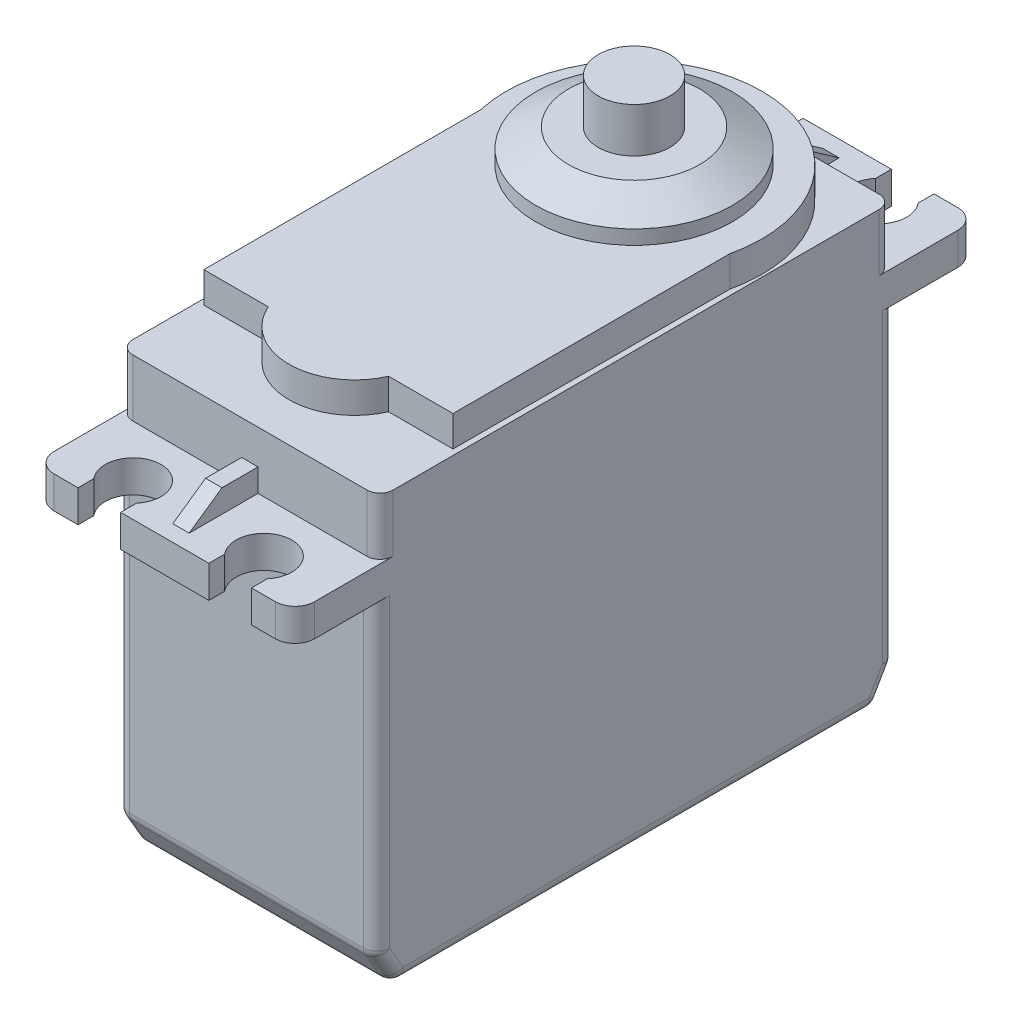
SolidWorks part; units mm, degrees
material "PA Type 6"
ref_plane "Front Plane" through (0, 0, 0) normal (0, 0, 1) x (1, 0, 0)
ref_plane "Top Plane" through (0, 0, 0) normal (0, 1, 0) x (1, 0, 0)
ref_plane "Right Plane" through (0, 0, 0) normal (1, 0, 0) x (0, 0, -1)
sketch "Sketch1" plane through (0, 0, 0) normal (0, 1, 0) x (1, 0, 0)
  line L1 (-10.0838, 10.1854) -> (10.0838, 10.1854)
  line L2 (-10.0838, 10.1854) -> (-10.0838, -30.0228)
  line L3 (-10.0838, -30.0228) -> (10.0838, -30.0228)
  line L4 (10.0838, 10.1854) -> (10.0838, -30.0228)
  point P4 (0, 10.1854)
  point P5 (0, 0)
  point P6 (7.6662, 10.1854)
  point P7 (0, 0)
  dimension "D1" = 20.1676
  dimension "D2" = 40.2082
  dimension "D4" = 10.1854
extrude "Extrude1" add sketch "Sketch1" along normal blind 26.4668
sketch "Sketch2" plane through (0, 26.4668, 0) normal (0, 1, 0) x (-1, 0, 0)
  line L0 (10.0838, 30.0228) -> (10.0838, 36.3474)
  line L1 (10.0838, 36.3474) -> (6.7183, 36.3474)
  line L2 (-10.0838, 36.3474) -> (-10.0838, 30.0228)
  line L3 (10.0838, -10.1854) -> (10.0838, -16.51)
  line L4 (10.0838, -10.1854) -> (10.0838, 30.0228)
  line L5 (10.0838, 30.0228) -> (-10.0838, 30.0228)
  line L6 (-10.0838, 30.0228) -> (-10.0838, -10.1854)
  line L7 (-10.0838, -10.1854) -> (10.0838, -10.1854)
  line L8 (10.0838, -10.1854) -> (10.0838, 30.0228)
  line L9 (10.0838, 30.0228) -> (-10.0838, 30.0228)
  line L10 (-10.0838, 30.0228) -> (-10.0838, -10.1854)
  line L11 (-10.0838, -10.1854) -> (10.0838, -10.1854)
  line L12 (10.0838, -16.51) -> (6.7183, -16.51)
  line L13 (-10.0838, -16.51) -> (-10.0838, -10.1854)
  line L14 (-6.7183, 35.1224) -> (-6.7183, 36.3474)
  line L15 (-3.4163, 35.1224) -> (-3.4163, 36.3474)
  line L16 (3.4163, 35.1224) -> (3.4163, 36.3474)
  line L17 (6.7183, 35.1224) -> (6.7183, 36.3474)
  line L18 (6.7183, -15.285) -> (6.7183, -16.51)
  line L19 (3.4163, -15.285) -> (3.4163, -16.51)
  line L20 (-3.4163, -15.285) -> (-3.4163, -16.51)
  line L21 (-6.7183, -15.285) -> (-6.7183, -16.51)
  line L22 (-6.7183, -16.51) -> (-10.0838, -16.51)
  line L23 (3.4163, -16.51) -> (-3.4163, -16.51)
  line L24 (-6.7183, 36.3474) -> (-10.0838, 36.3474)
  line L25 (3.4163, 36.3474) -> (-3.4163, 36.3474)
  arc A0 (3.4163, 35.1224) -> (6.7183, 35.1224) centre (5.0673, 33.7312) ccw
  arc A1 (-6.7183, 35.1224) -> (-3.4163, 35.1224) centre (-5.0673, 33.7312) ccw
  arc A2 (-3.4163, -15.285) -> (-6.7183, -15.285) centre (-5.0673, -13.8938) ccw
  arc A3 (6.7183, -15.285) -> (3.4163, -15.285) centre (5.0673, -13.8938) ccw
  point P7 (0, -16.51)
  point P9 (0, 0)
  point P11 (0, 0)
  line M5 (10.0838, -10.1854) -> (10.0838, 30.0228)
  line M6 (10.0838, 30.0228) -> (-10.0838, 30.0228)
  line M7 (-10.0838, 30.0228) -> (-10.0838, -10.1854)
  line M8 (-10.0838, -10.1854) -> (10.0838, -10.1854)
  dimension "D2" = 4.318
  dimension "D9" = 3.302
  dimension "D4" = 10.1346
  dimension "D5" = 47.625
  dimension "D6" = 3.7084
  dimension "D7" = 6.3246
  dimension "D8" = 6.3246
  dimension "D10" = 3.302
  dimension "D11" = 1.651
  dimension "D12" = 1.651
  dimension "D1" = 0
extrude "Extrude2" add sketch "Sketch2" along normal blind 2.4892 contours M8 M5 M6 M7 | A3 L18 L12 L3 L13 L22 L21 A2 L20 L23 L19 M8 | A1 L14 L24 L2 L0 L1 L17 A0 L16 L25 L15 M6
sketch "Sketch3" plane through (0, 28.956, 0) normal (0, 1, 0) x (-1, 0, 0)
  line L4 (10.0838, -10.1854) -> (10.0838, 30.0228)
  line L5 (-10.0838, -10.1854) -> (10.0838, -10.1854)
  line L6 (-10.0838, 30.0228) -> (-10.0838, -10.1854)
  line L7 (10.0838, 30.0228) -> (-10.0838, 30.0228)
  line L8 (10.0838, -10.1854) -> (10.0838, 30.0228)
  line L9 (-10.0838, -10.1854) -> (10.0838, -10.1854)
  line L10 (-10.0838, 30.0228) -> (-10.0838, -10.1854)
  line L11 (10.0838, 30.0228) -> (-10.0838, 30.0228)
  dimension "D1" = 0
extrude "Extrude3" add sketch "Sketch3" along normal blind 4.445
sketch "Sketch11" plane through (0, 33.401, 0) normal (0, 1, 0) x (1, 0, 0)
  line L0 (-10.0838, 10.1854) -> (-10.0838, -30.0228) construction
  line L1 (-10.0838, -30.0228) -> (10.0838, -30.0228)
  line L2 (-10.0838, -30.0228) -> (-10.0838, 10.1854)
  line L3 (-10.0838, 10.1854) -> (10.0838, 10.1854)
  line L4 (10.0838, -30.0228) -> (10.0838, 10.1854)
  line L5 (-10.0838, -30.0228) -> (10.0838, 10.1854) construction
  line L6 (-10.0838, 10.1854) -> (10.0838, -30.0228) construction
  line L7 (-10.0838, -29.7561) -> (10.0838, -29.7561)
  line L8 (-10.0838, -29.7561) -> (-10.0838, 9.9187)
  line L9 (-10.0838, 9.9187) -> (10.0838, 9.9187)
  line L10 (10.0838, -29.7561) -> (10.0838, 9.9187)
  line L11 (-10.0838, -29.7561) -> (10.0838, 9.9187) construction
  line L12 (-10.0838, 9.9187) -> (10.0838, -29.7561) construction
  point P0 (0, -9.9187)
  point P5 (0, -9.9187)
  point P11 (0, 0)
  point P12 (4.0444, -9.9187)
  line M4 (-10.0838, -30.0228) -> (10.0838, -30.0228)
  line M5 (10.0838, -30.0228) -> (10.0838, 10.1854)
  line M6 (10.0838, 10.1854) -> (-10.0838, 10.1854)
  line M7 (-10.0838, 10.1854) -> (-10.0838, -30.0228)
  dimension "D1" = 39.6748
extrude "Cut-Extrude2" cut sketch "Sketch11" against normal up to surface (4.445 mm away) contours L9 M7 M5 M6 | L7 L2 M4 M5
sketch "Sketch4" plane through (0, 33.401, 0) normal (0, 1, 0) x (-1, 0, 0)
  line L0 (9.652, 2.2288) -> (9.652, 23.6728)
  line L1 (9.652, 23.6728) -> (4.6559, 23.6728)
  line L2 (-9.652, 23.6728) -> (-9.652, 2.2288)
  line L4 (-4.6559, 23.6728) -> (-9.652, 23.6728)
  arc A0 (-9.652, 2.2288) -> (9.652, 2.2288) centre (0, 0) ccw
  arc A1 (4.6559, 23.6728) -> (-4.6559, 23.6728) centre (0, 21.6408) ccw
  dimension "D1" = 19.812
  dimension "D5" = 5.08
  dimension "D2" = 6.35
  dimension "D3" = 19.304
  dimension "D4" = 9.652
  dimension "D6" = 2.032
extrude "Extrude4" add sketch "Sketch4" along normal blind 2.3813
ref_plane "Plane1" through (0, 38.354, 0) normal (0, -1, 0) x (1, 0, 0)
sketch "Sketch5" plane through (0, 35.7823, 0) normal (0, 1, 0) x (-1, 0, 0)
  circle A0 centre (0, 0) radius 7.62
  dimension "D1" = 15.24
extrude "Extrude5" add sketch "Sketch5" along normal up to surface (2.5717 mm away) up to plane "Plane1"
chamfer "Chamfer1" distance 2.54 angle 30 1 edges at (0, 38.354, -7.62)
sketch "Sketch7" plane through (0, 0, 0) normal (1, 0, 0) x (0, 0, -1)
  line L0 (15.2527, 28.956) -> (12.7127, 30.734)
  line L1 (9.9187, 28.956) -> (9.9187, 33.401) construction
  line L4 (12.7127, 30.734) -> (9.9187, 30.734)
  line L6 (16.51, 28.956) -> (9.9187, 28.956) construction
  line L7 (9.9187, 30.734) -> (9.9187, 28.956)
  line L8 (9.9187, 28.956) -> (15.2527, 28.956)
  point P3 (0, 0)
  point P8 (0, 0)
  dimension "D1" = 1.778
  dimension "D2" = 2.794
  dimension "D3" = 5.334
extrude "Extrude6" add sketch "Sketch7" along normal mid plane 1.27
ref_plane "Plane2" through (0, 0, 9.9187) normal (0, 0, -1) x (-1, 0, 0)
mirror "Mirror1" about plane through (0, 0, 9.9187) normal (0, 0, -1) of "Extrude6"
sketch "Sketch8" plane through (0, 38.354, 0) normal (0, 1, 0) x (-1, 0, 0)
  circle A0 centre (0, 0) radius 2.7781
  dimension "D1" = 5.5562
extrude "Extrude7" add sketch "Sketch8" along normal blind 3.4544
chamfer "Chamfer2" distance 2.54 angle 30 2 edges at (0, 0, 30.0228) (0, 0, -10.1854)
fillet "Fillet1" radius 1.016 18 edges at (10.0838, 0, 9.9187) (10.0838, 1.27, -9.4522) (0, 0, -8.7189) (0, 2.54, -10.1854) (-10.0838, 1.27, -9.4522) (10.0838, 1.27, 29.2896) (0, 2.54, 30.0228) (-10.0838, 0, 9.9187) (0, 0, 28.5563) (-10.0838, 1.27, 29.2896) (10.0838, 31.1785, 29.7561) (-10.0838, 31.1785, 29.7561) (10.0838, 31.1785, -9.9187) (-10.0838, 31.1785, -9.9187)
fillet "Fillet2" radius 1.524 4 edges at (-10.0838, 27.7114, 36.3474) (10.0838, 27.7114, 36.3474) (-10.0838, 27.7114, -16.51) (10.0838, 27.7114, -16.51)
sketch "Sketch9" plane through (0, 0, -10.1854) normal (0, 0, -1) x (-1, 0, 0)
  line L1 (-3.175, 5.588) -> (3.175, 5.588)
  line L2 (-3.175, 5.588) -> (-3.175, 3.048)
  line L3 (-3.175, 3.048) -> (3.175, 3.048)
  line L4 (3.175, 5.588) -> (3.175, 3.048)
  dimension "D1" = 6.35
  dimension "D2" = 2.54
  dimension "D3" = 3.048
  dimension "D4" = 3.175
extrude "Extrude8" add sketch "Sketch9" along normal blind 2.3813
sketch "Sketch10" plane through (0, 0, -12.5667) normal (0, 0, -1) x (-1, 0, 0)
  line L8 (-2.54, 4.953) -> (-2.54, 3.683)
  line L9 (-2.54, 3.683) -> (2.54, 3.683)
  line L10 (2.54, 3.683) -> (2.54, 4.953)
  line L11 (2.54, 4.953) -> (-2.54, 4.953)
  line L12 (-2.54, 4.953) -> (-2.54, 3.683)
  line L13 (-2.54, 3.683) -> (2.54, 3.683)
  line L14 (2.54, 3.683) -> (2.54, 4.953)
  line L15 (2.54, 4.953) -> (-2.54, 4.953)
  dimension "D1" = 0.635
extrude "Cut-Extrude1" cut sketch "Sketch10" against normal up to surface (2.3813 mm away) up to face at (2.2669, 14.6395, -10.1854)
